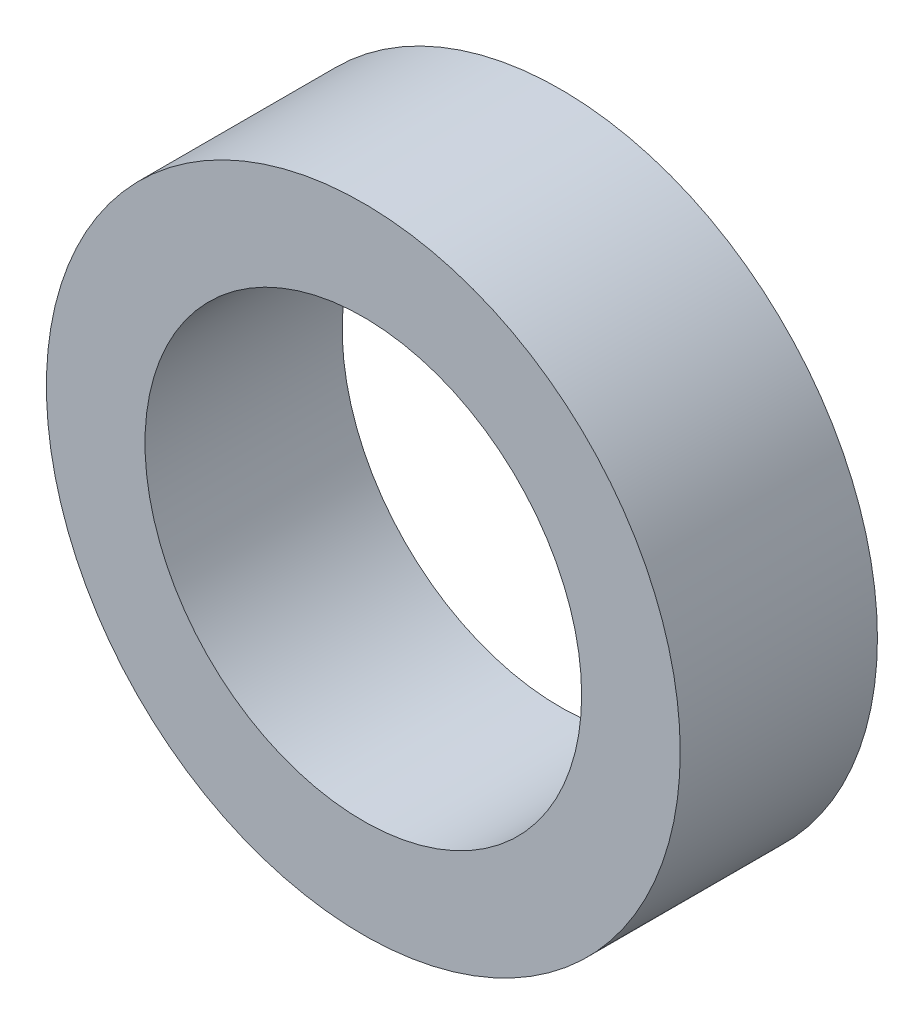
SolidWorks part; units mm, degrees
ref_plane "正面" through (0, 0, 0) normal (0, 0, 1) x (1, 0, 0)
ref_plane "平面" through (0, 0, 0) normal (0, 1, 0) x (1, 0, 0)
ref_plane "右側面" through (0, 0, 0) normal (1, 0, 0) x (0, 0, -1)
sketch "ｽｹｯﾁ1" plane through (0, 0, 0) normal (0, 0, 1) x (1, 0, 0)
  circle A0 centre (0, 0) radius 4.5
  circle A1 centre (0, 0) radius 3.1
  point P5 (0, -0.2982)
  dimension "D1" = 6.2
  dimension "D2" = 9
extrude "ﾎﾞｽ - 押し出し1" add sketch "ｽｹｯﾁ1" along normal blind 2.8
